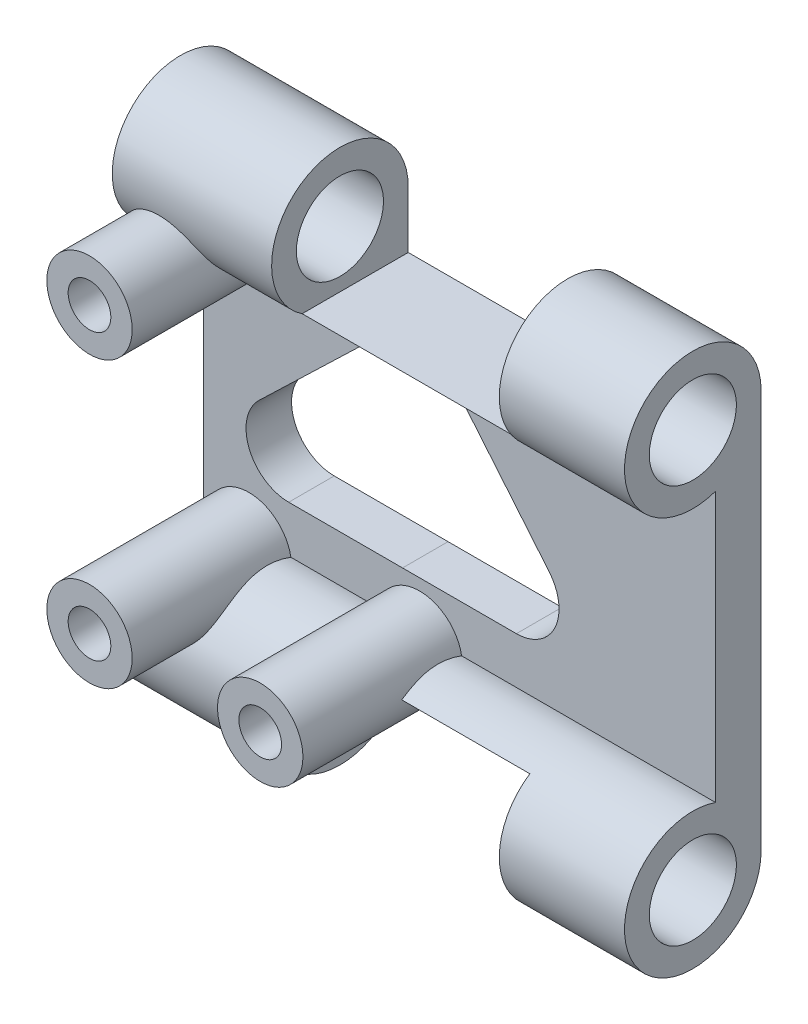
SolidWorks part; units mm, degrees
material "ABS"
ref_plane "Plano frontal" through (0, 0, 0) normal (0, 0, 1) x (1, 0, 0)
ref_plane "Plano superior" through (0, 0, 0) normal (0, 1, 0) x (1, 0, 0)
ref_plane "Plano direito" through (0, 0, 0) normal (1, 0, 0) x (0, 0, -1)
sketch "Esboço2" plane through (0, 0, 0) normal (1, 0, 0) x (0, 0, -1)
  line L0 (0, 35) -> (0, -35) construction
  line L1 (12, 35) -> (12, -35)
  line L2 (4, -23.6863) -> (4, 23.6863)
  circle A0 centre (0, 35) radius 7.65
  arc A1 (12, 35) -> (4, 23.6863) centre (0, 35) ccw
  arc A2 (4, -23.6863) -> (12, -35) centre (0, -35) ccw
  circle A3 centre (0, -35) radius 7.65
  circle A4 centre (0, 35) radius 4 construction
  circle A5 centre (0, -35) radius 4 construction
  point P8 (0, 0)
  dimension "D1" = 15.3
  dimension "D2" = 8
  dimension "D3" = 24
  dimension "D4" = 70
  dimension "D5" = 8
extrude "Ressalto-extrusão1" add sketch "Esboço2" along normal blind 90
sketch "Esboço4" plane through (0, 0, -4) normal (0, 0, 1) x (1, 0, 0)
  line L0 (0, 23.6863) -> (0, -23.6863) construction
  line L1 (15, -8) -> (55, -8) construction
  line L2 (9.8006, -2.5948) -> (29.7208, 16.5672)
  line L3 (45.0814, 15.7038) -> (60.7724, -3.2116)
  line L4 (15.0002, -15.5) -> (35, -15.4993)
  line L5 (35, -15.4993) -> (54.9998, -15.5)
  circle A0 centre (8, 25) radius 1.75
  circle A1 centre (8, -25) radius 1.75
  circle A2 centre (38, -25) radius 1.75
  arc A3 (45.0814, 15.7038) -> (29.7208, 16.5672) centre (37, 9) ccw
  arc A4 (9.8006, -2.5948) -> (15.0002, -15.5) centre (15, -8) ccw
  arc A5 (54.9998, -15.5) -> (60.7724, -3.2116) centre (55, -8) ccw
  point P9 (30, -14.9426)
  point P11 (0, 0)
  point P14 (0, 0)
  dimension "D1" = 3.5
  dimension "D6" = 15
  dimension "D7" = 21
  dimension "D2" = 50
  dimension "D3" = 30
  dimension "D4" = 8
  dimension "D5" = 25
  dimension "D8" = 17
  dimension "D9" = 40
  dimension "D10" = 7
  dimension "D11" = 22
  dimension "D12" = 17
extrude "Corte-extrusão1" cut sketch "Esboço4" against normal through all and the other way through all
sketch "Esboço5" plane through (0, 0, -4) normal (0, 0, 1) x (1, 0, 0)
  line L0 (68, -25) -> (68, -50)
  line L1 (68, -50) -> (28, -50)
  line L2 (28, -50) -> (28, -25)
  line L3 (28, -25) -> (68, -25)
  line L6 (0, -25) -> (90, -25) construction
  line L7 (0, -23) -> (0, -47) construction
  line L8 (0, 0) -> (101.2867, 0) construction
  line L9 (0, 25) -> (90, 25) construction
  line L10 (28, 25) -> (68, 25)
  line L11 (28, 50) -> (28, 25)
  line L12 (68, 50) -> (28, 50)
  line L13 (68, 25) -> (68, 50)
  circle A0 centre (8, -25) radius 1.75 construction
  dimension "D1" = 40
  dimension "D2" = 20
  dimension "D3" = 25
  dimension "D4" = 25
extrude "Corte-extrusão2" cut sketch "Esboço5" along normal through all and the other way blind 20 from offset 5 offset against normal yes
sketch "Esboço6" plane through (0, 0, -4) normal (0, 0, 1) x (1, 0, 0)
  circle A0 centre (8, 25) radius 1.75 construction
  circle A1 centre (38, -25) radius 3.75
  circle A2 centre (8, -25) radius 3.75
  circle A3 centre (8, 25) radius 3.75
  circle A4 centre (8, 25) radius 7.5
  circle A5 centre (8, -25) radius 7.5
  circle A6 centre (38, -25) radius 7.5
  dimension "D1" = 7.5
  dimension "D2" = 15
extrude "Ressalto-extrusão2" add sketch "Esboço6" along normal blind 28 and the other way up to surface
sketch "Esboço7" plane through (0, 0, 0) normal (-1, 0, 0) x (0, 0, 1)
  circle A0 centre (0, 35) radius 7.65
  circle A1 centre (0, -35) radius 7.65
extrude "Corte-extrusão3" cut sketch "Esboço7" against normal up to surface (28 mm away) up to face at (28, -35, 7.65)
sketch "Esboço8" plane through (0, 0, 0) normal (-1, 0, 0) x (0, 0, 1)
  circle A0 centre (0, -35) radius 4.5
  dimension "D1" = 9
extrude "Corte-extrusão4" cut sketch "Esboço8" against normal through all
